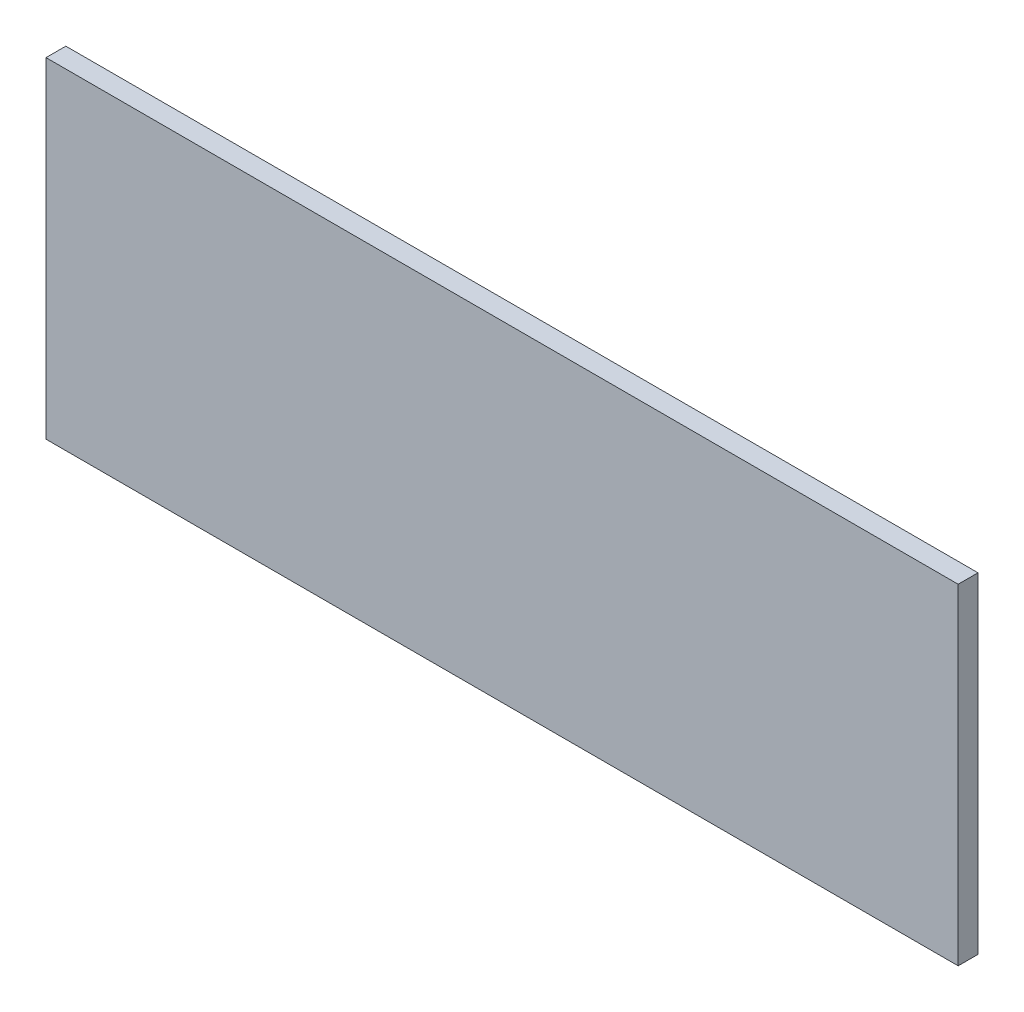
SolidWorks part; units mm, degrees
ref_plane "Alzado" through (0, 0, 0) normal (0, 0, 1) x (1, 0, 0)
ref_plane "Planta" through (0, 0, 0) normal (0, 1, 0) x (1, 0, 0)
ref_plane "Vista lateral" through (0, 0, 0) normal (1, 0, 0) x (0, 0, -1)
sketch "Croquis1" plane through (0, 0, 0) normal (0, 0, 1) x (1, 0, 0)
  line L1 (-690, -250) -> (690, -250)
  line L2 (-690, -250) -> (-690, 250)
  line L3 (-690, 250) -> (690, 250)
  line L4 (690, -250) -> (690, 250)
  line L5 (-690, -250) -> (690, 250) construction
  line L6 (-690, 250) -> (690, -250) construction
  point P0 (0, 0)
  dimension "D1" = 1380
  dimension "D2" = 500
extrude "Saliente-Extruir1" add sketch "Croquis1" along normal blind 30
sketch "Croquis2" plane through (0, 0, 0) normal (0, 0, -1) x (-1, 0, 0)
  line L5 (-427.1222, -89.131) -> (-637.1222, -89.131)
  line L6 (-427.1222, -89.131) -> (-427.1222, 207.869)
  line L7 (-427.1222, 207.869) -> (-637.1222, 207.869)
  line L8 (-637.1222, -89.131) -> (-637.1222, 207.869)
  line L9 (-427.1222, -89.131) -> (-637.1222, 207.869) construction
  line L10 (-427.1222, 207.869) -> (-637.1222, -89.131) construction
  circle A0 centre (-256.5327, 167.998) radius 40
  point P2 (-532.1222, 59.369)
  point P3 (-532.1222, 59.369)
  point P8 (0, 0)
  point P9 (-256.5327, 167.998)
  point P10 (0, 0)
  dimension "D1" = 80
  dimension "D2" = 297
  dimension "D3" = 210
extrude "Cortar-Extruir3" cut sketch "Croquis2" against normal blind 10
